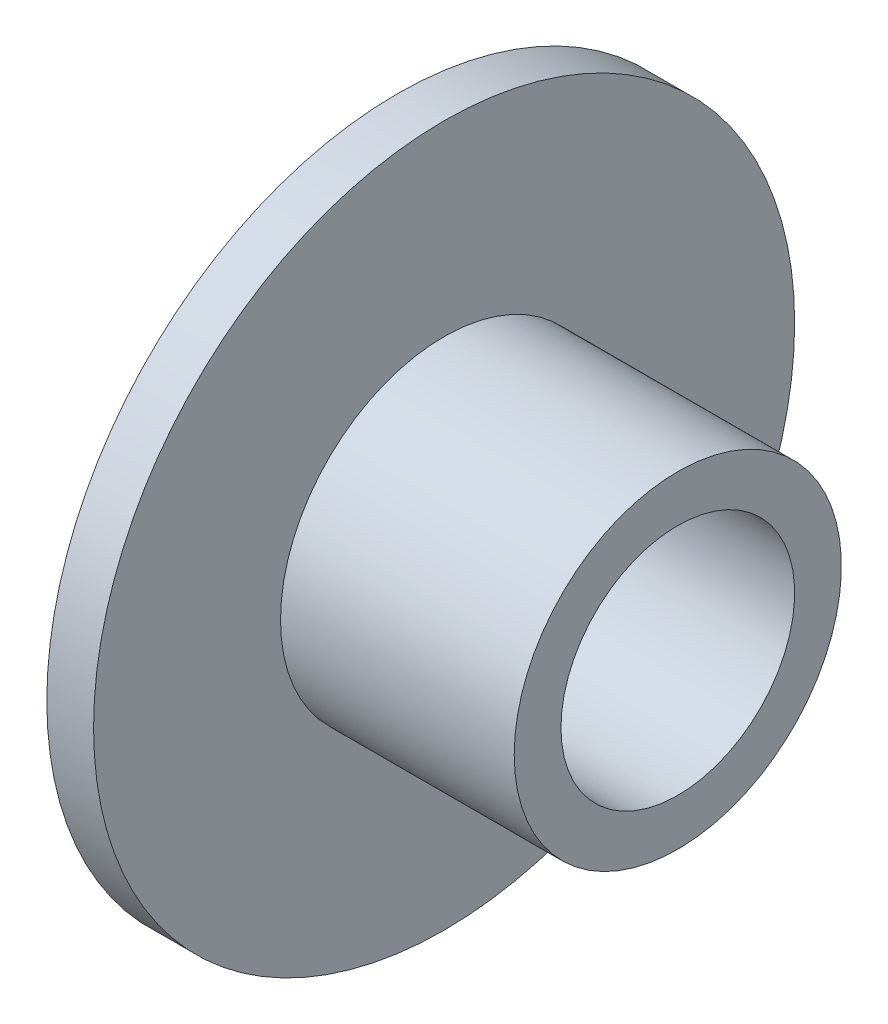
SolidWorks part; units mm, degrees
ref_plane "Front Plane" through (0, 0, 0) normal (0, 0, 1) x (1, 0, 0)
ref_plane "Top Plane" through (0, 0, 0) normal (0, 1, 0) x (1, 0, 0)
ref_plane "Right Plane" through (0, 0, 0) normal (1, 0, 0) x (0, 0, -1)
sketch "Sketch2" plane through (0, 0, 0) normal (0, 1, 0) x (1, 0, 0)
  line L1 (22.586, 17.434) -> (24.586, 17.434)
  line L2 (24.586, 17.434) -> (24.586, 9.434)
  line L3 (24.586, 9.434) -> (34.586, 9.434)
  line L7 (22.586, 15.434) -> (22.586, 7.434)
  line L8 (22.586, 7.434) -> (34.586, 7.434)
  line L9 (22.586, 15.434) -> (22.586, 17.434)
  line L10 (34.586, 7.434) -> (34.586, 9.434)
  line L11 (22.586, 7.434) -> (22.586, 2.434) construction
  line L12 (22.586, 2.434) -> (44.3854, 2.434) construction
  dimension "D1" = 2
  dimension "D2" = 8
  dimension "D3" = 10
  dimension "D4" = 5
  dimension "D5" = 2
  dimension "D6" = 2
revolve "Revolve1" add sketch "Sketch2" angle 360 about L12
